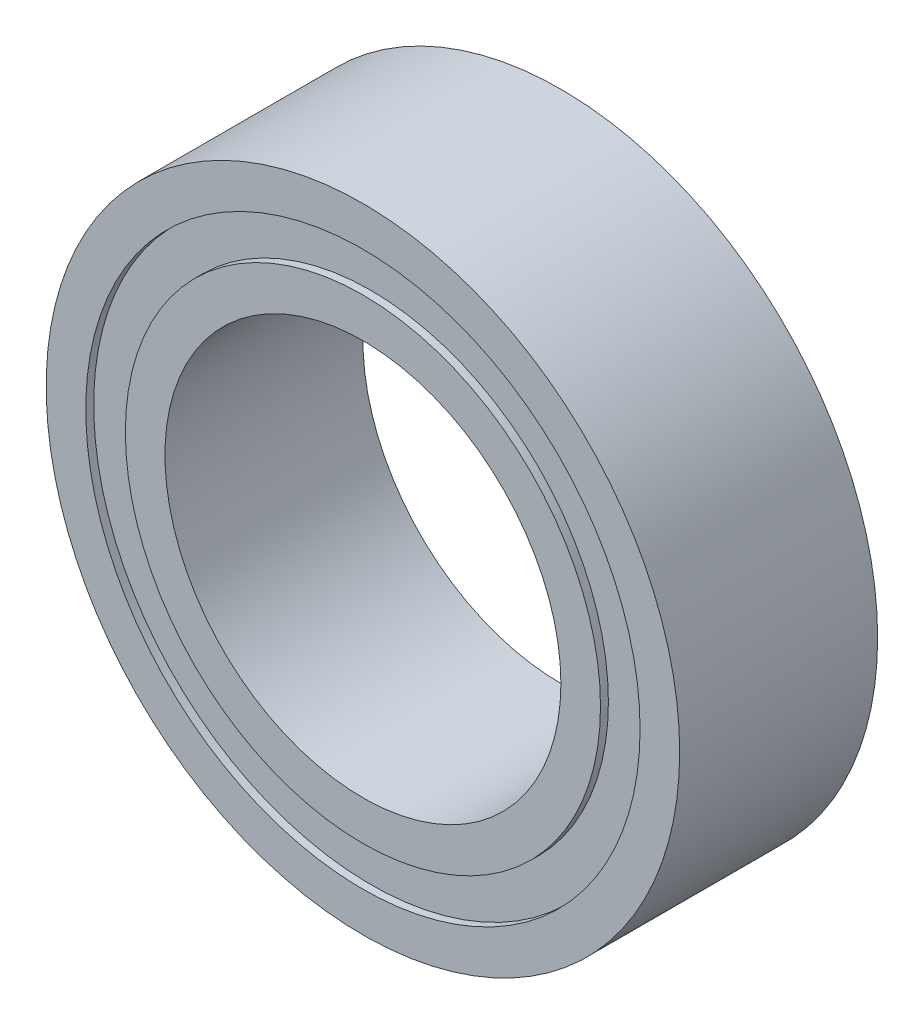
SolidWorks part; units mm, degrees
ref_plane "Front Plane" through (0, 0, 0) normal (0, 0, 1) x (1, 0, 0)
ref_plane "Top Plane" through (0, 0, 0) normal (0, 1, 0) x (1, 0, 0)
ref_plane "Right Plane" through (0, 0, 0) normal (1, 0, 0) x (0, 0, -1)
sketch "Sketch1" plane through (0, 0, 0) normal (0, 0, 1) x (1, 0, 0)
  circle A0 centre (0, 0) radius 4
  circle A1 centre (0, 0) radius 2.5
  dimension "D1" = 8
  dimension "D2" = 5
extrude "Boss-Extrude1" add sketch "Sketch1" along normal blind 2.5
sketch "Sketch2" plane through (0, 0, 0) normal (0, 0, -1) x (-1, 0, 0)
  circle A0 centre (0, 0) radius 3
  circle A1 centre (0, 0) radius 3.5
  dimension "D1" = 7
  dimension "D2" = 6
extrude "Cut-Extrude1" cut sketch "Sketch2" against normal blind 0.1
sketch "Sketch3" plane through (0, 0, 2.5) normal (0, 0, 1) x (1, 0, 0)
  circle A1 centre (0, 0) radius 3.5
  circle A2 centre (0, 0) radius 3.5
  circle A3 centre (0, 0) radius 3
  circle A4 centre (0, 0) radius 3
  dimension "D1" = 0
  dimension "D2" = 0
extrude "Cut-Extrude2" cut sketch "Sketch3" against normal blind 0.1
equation "\"I\" = 5mm"
equation "\"E\"= 8mm"
equation "\"T\"= 2.5mm"
equation "\"D1@Sketch1\"=\"E\""
equation "\"D2@Sketch1\"=\"I\""
equation "\"D1@Sketch2\"=\"E\"-1"
equation "\"D2@Sketch2\"=\"I\"+1"
equation "\"D1@Boss-Extrude1\"=\"T\""
